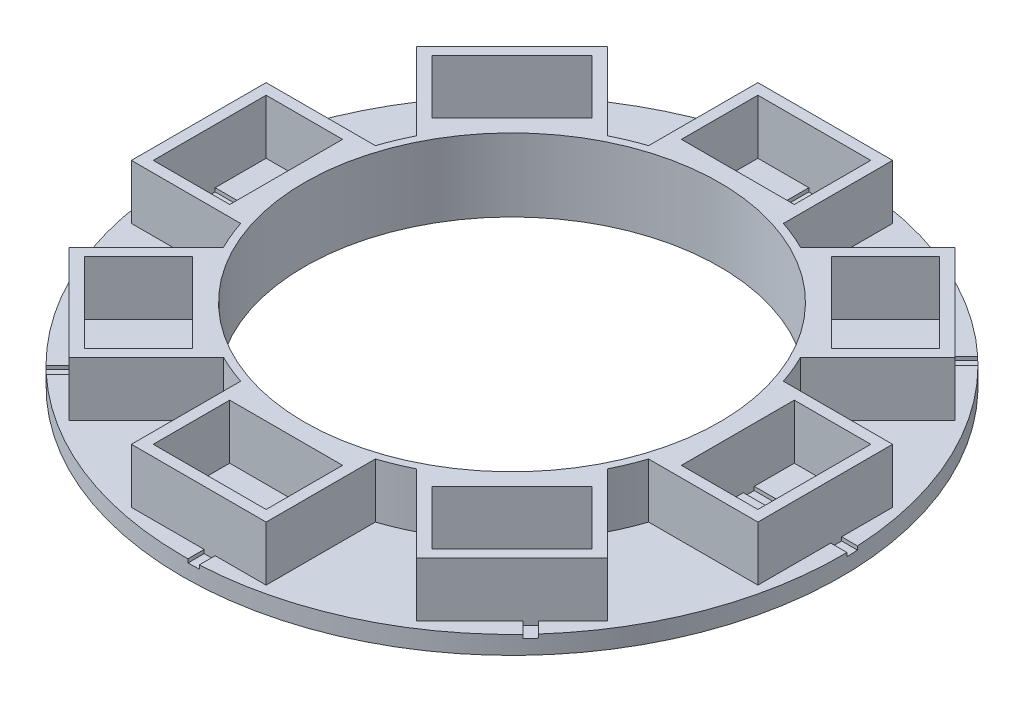
SolidWorks part; units mm, degrees
ref_plane "Front Plane" through (0, 0, 0) normal (0, 0, 1) x (1, 0, 0)
ref_plane "Top Plane" through (0, 0, 0) normal (0, 1, 0) x (1, 0, 0)
ref_plane "Right Plane" through (0, 0, 0) normal (1, 0, 0) x (0, 0, -1)
sketch "Sketch2" plane through (0, 0, 0) normal (1, 0, 0) x (0, 0, -1)
  line L0 (0, 80.233) -> (0, -59.3369) construction
  line L2 (-90.5, 4.1219) -> (-57, 4.1219)
  line L3 (-57, 6.1219) -> (-57, 24.1219)
  line L4 (-57, 24.1219) -> (-59, 24.1219)
  line L5 (-59, 24.1219) -> (-59, 9.1219)
  line L6 (-59, 9.1219) -> (-90.5, 9.1219)
  line L12 (-57, 6.1219) -> (-57, 4.1219)
  line L13 (-90.5, 9.1219) -> (-90.5, 4.1219)
  dimension "D2" = 114
  dimension "D5" = 2
  dimension "D9" = 20
revolve "Revolve1" add sketch "Sketch2" angle 360 about L0
sketch "Sketch3" plane through (0, 9.1219, 0) normal (0, 1, 0) x (1, 0, 0)
  line L52 (-114.9809, -1.5) -> (-58.9809, -1.5)
  line L53 (-114.9809, -1.5) -> (-114.9809, 1.5)
  line L54 (-114.9809, 1.5) -> (-58.9809, 1.5)
  line L55 (-58.9809, -1.5) -> (-58.9809, 1.5)
  line L56 (-114.9809, -1.5) -> (-58.9809, 1.5) construction
  line L57 (-114.9809, 1.5) -> (-58.9809, -1.5) construction
  line L61 (-138.3253, 0) -> (168.8553, 0) construction
  line L75 (-82.986, 81.7436) -> (-80.8646, 83.8649)
  line L84 (-82.986, 81.7436) -> (-43.388, 42.1456)
  line L85 (-43.388, 42.1456) -> (-41.2667, 44.2669)
  line L98 (0, -107.9978) -> (0, -137.9498) construction
  line L114 (-80.8646, 83.8649) -> (-41.2667, 44.2669)
  line L115 (-1.5, 117.9819) -> (1.5, 117.9819)
  line L116 (-1.5, 117.9819) -> (-1.5, 61.9819)
  line L117 (-1.5, 61.9819) -> (1.5, 61.9819)
  line L118 (1.5, 117.9819) -> (1.5, 61.9819)
  line L119 (81.7436, 85.9869) -> (83.8649, 83.8656)
  line L120 (81.7436, 85.9869) -> (42.1456, 46.3889)
  line L121 (42.1456, 46.3889) -> (44.2669, 44.2676)
  line L122 (83.8649, 83.8656) -> (44.2669, 44.2676)
  line L123 (117.9819, 4.5009) -> (117.9819, 1.5009)
  line L124 (117.9819, 4.5009) -> (61.9819, 4.5009)
  line L125 (61.9819, 4.5009) -> (61.9819, 1.5009)
  line L126 (117.9819, 1.5009) -> (61.9819, 1.5009)
  line L127 (85.9869, -78.7427) -> (83.8656, -80.864)
  line L128 (85.9869, -78.7427) -> (46.3889, -39.1447)
  line L129 (46.3889, -39.1447) -> (44.2676, -41.266)
  line L130 (83.8656, -80.864) -> (44.2676, -41.266)
  line L131 (4.5009, -114.9809) -> (1.5009, -114.9809)
  line L132 (4.5009, -114.9809) -> (4.5009, -58.9809)
  line L133 (4.5009, -58.9809) -> (1.5009, -58.9809)
  line L134 (1.5009, -114.9809) -> (1.5009, -58.9809)
  line L135 (-78.7427, -82.986) -> (-80.864, -80.8646)
  line L136 (-78.7427, -82.986) -> (-39.1447, -43.388)
  line L137 (-39.1447, -43.388) -> (-41.266, -41.2667)
  line L138 (-80.864, -80.8646) -> (-41.266, -41.2667)
  circle A8 centre (0, 0) radius 59 construction
  point P0 (-86.9809, 0)
  point P21 (0, 0)
  point P33 (0, 0)
  point P36 (-5.0017, -8.6633)
  point P44 (0, 0)
  point P48 (-0.0332, 4.9999)
  point P52 (0, 0)
  point P56 (1.5005, 1.5005)
  dimension "D1" = 56
  dimension "D2" = 3
  dimension "D3" = 8
extrude "Cut-Extrude1" cut sketch "Sketch3" against normal blind 1
sketch "Sketch4" plane through (0, 9.1219, 0) normal (0, 1, 0) x (1, 0, 0)
  line L0 (18.5, 86.03) -> (18.5, 59.03)
  line L1 (-15.5, 83.03) -> (15.5, 83.03)
  line L2 (-15.5, 83.03) -> (-15.5, 62.03)
  line L5 (-15.5, 83.03) -> (15.5, 62.03) construction
  line L6 (-15.5, 62.03) -> (15.5, 83.03) construction
  line L7 (18.5, 59.03) -> (18.5, 55.7077)
  line L8 (-18.5, 86.03) -> (18.5, 86.03)
  line L9 (-18.5, 86.03) -> (-18.5, 59.03)
  line L10 (-18.5, 86.03) -> (-18.5, 62.03) construction
  line L11 (0, 82.143) -> (0, 47.916) construction
  line L12 (15.5, 83.03) -> (15.5, 62.03)
  line L13 (15.5, 83.03) -> (15.5, 62.03) construction
  line L14 (18.5, 86.03) -> (18.5, 62.03) construction
  line L15 (-15.5, 62.03) -> (15.5, 62.03)
  line L17 (-18.5, 59.03) -> (-18.5, 55.7077)
  arc A0 (-18.5, 55.7077) -> (18.5, 55.7077) centre (0, -11.4441) cw
  point P0 (0, 72.53)
  dimension "D4" = 72.53
  dimension "D1" = 21
  dimension "D2" = 31
  dimension "D3" = 3
extrude "Boss-Extrude1" add sketch "Sketch4" along normal up to surface and the other way up to surface up to face at (0, 24.1219, 59) other way up to face at (-52.9375, 8.1219, -53.8165)
pattern_circular "CirPattern1" count 8 over 360 about axis through (0, 0, 0) along (0, 1, 0) of "Boss-Extrude1"
